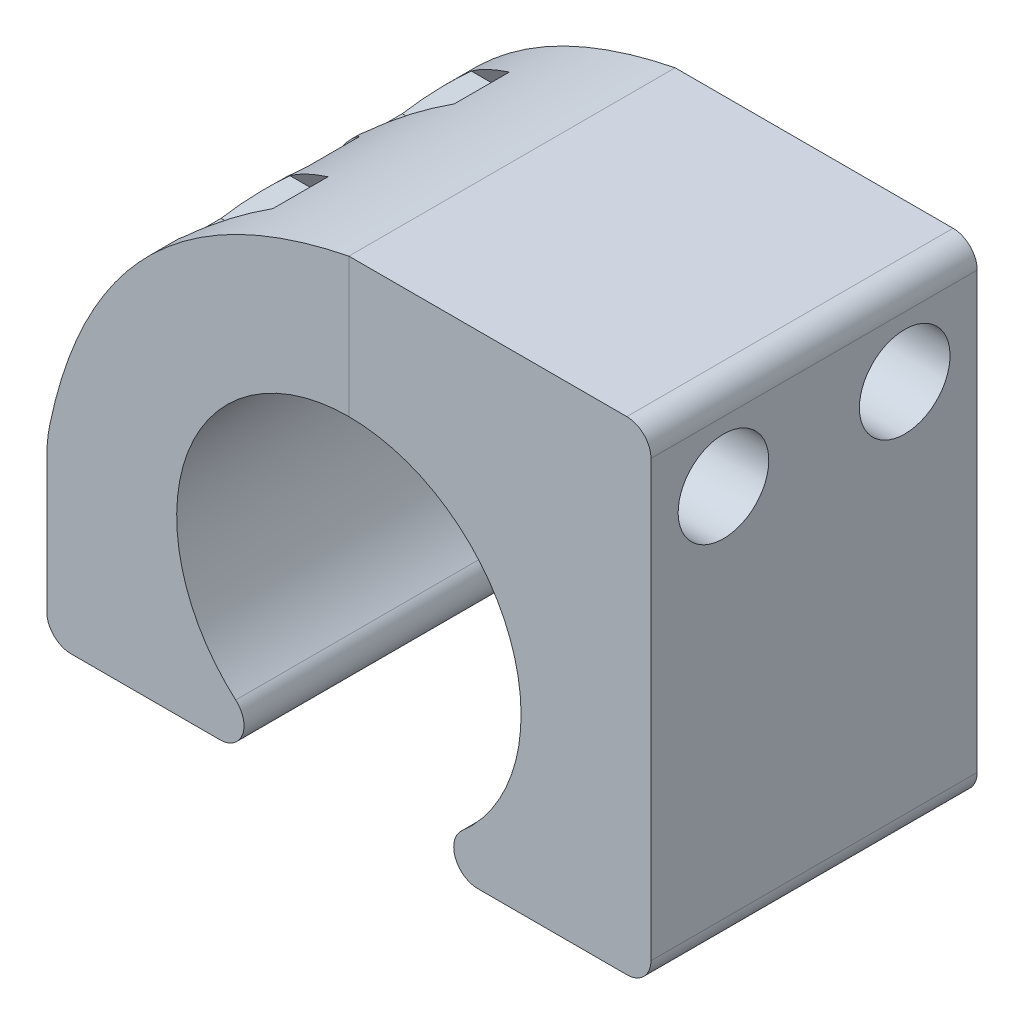
SolidWorks part; units mm, degrees
ref_plane "Front Plane" through (0, 0, 0) normal (0, 0, 1) x (1, 0, 0)
ref_plane "Top Plane" through (0, 0, 0) normal (0, 1, 0) x (1, 0, 0)
ref_plane "Right Plane" through (0, 0, 0) normal (1, 0, 0) x (0, 0, -1)
sketch "Sketch1" plane through (0, 0, 0) normal (0, 0, 1) x (1, 0, 0)
  line L0 (10.6771, -14.25) -> (25, -14.25)
  line L1 (-25, -14.25) -> (-10.6771, -14.25)
  line L2 (-25, -14.25) -> (-25, 25.75)
  line L3 (-25, 25.75) -> (25, 25.75)
  line L4 (25, -14.25) -> (25, 25.75)
  arc A0 (9.363, -10.7423) -> (-9.363, -10.7423) centre (0, 0) ccw
  arc A1 (9.363, -10.7423) -> (10.6771, -14.25) centre (10.6771, -12.25) ccw
  arc A2 (-9.363, -10.7423) -> (-10.6771, -14.25) centre (-10.6771, -12.25) cw
  point P4 (0, 25.75)
  point P9 (0, -14.25)
  dimension "D1" = 28.5
  dimension "D5" = 2
  dimension "D6" = 50
  dimension "D2" = 40
  dimension "D3" = 14.25
  dimension "D4" = 14.25
extrude "Boss-Extrude1" add sketch "Sketch1" along normal mid plane 27
sketch "Sketch2" plane through (0, 0, 13.5) normal (0, 0, 1) x (1, 0, 0)
  line L0 (0, 25.75) -> (0, 0)
  line L1 (25, 25.75) -> (-25, 25.75) construction
fillet "Fillet1" radius 2 3 edges at (25, -14.25, 0) (25, 25.75, 0) (-25, -14.25, 0)
split "Split1" trim tools "Sketch2" bodies to split 101 resulting bodies 102 103
sketch "Sketch3" plane through (25, 0, 0) normal (1, 0, 0) x (0, 0, -1)
  line L0 (-13.5, 25.75) -> (13.5, 25.75) construction
  line L1 (0, 0) -> (0, 23.0503) construction
  circle A0 centre (-7.5, 18.75) radius 3.75
  circle A1 centre (7.5, 18.75) radius 3.75
  dimension "D1" = 7.5
  dimension "D2" = 7
  dimension "D3" = 15
extrude "Cut-Extrude1" cut sketch "Sketch3" against normal offset from surface (10 mm away) 15 up to face at (0, 20, 0)
sketch "Sketch7" plane through (15, 0, 0) normal (1, 0, 0) x (0, 0, -1)
  line L0 (0, 0) -> (0, 5.8858) construction
  circle A0 centre (-7.5, 18.75) radius 2.25
  circle A1 centre (7.5, 18.75) radius 2.25
  dimension "D1" = 4.5
extrude "Cut-Extrude3" cut sketch "Sketch7" against normal up to next (15 mm away)
sketch "Sketch6" plane through (0, 0, 13.5) normal (0, 0, 1) x (1, 0, 0)
  line L0 (-25, 25.75) -> (-25, -12.25) construction
  line L1 (0, 25.75) -> (-25, 25.75) construction
  line L2 (-25, 25.75) -> (-25, 0)
  line L3 (0, 25.75) -> (-25, 25.75)
  spline S0 degree 2 poles (0, 25.75) (-21.1639, 21.5385) (-25, 0) knots 0 0 0 1 1 1
extrude "Cut-Extrude2" cut sketch "Sketch6" against normal up to next (27 mm away)
fillet "Fillet2" radius 12 1 edges at (-25, 0, 0)
sketch "Sketch8" plane through (0, 0, 0) normal (1, 0, 0) x (0, 0, -1)
  circle A0 centre (7.5, 18.75) radius 2.25 construction
  circle A1 centre (-7.5, 18.75) radius 2.25 construction
  circle A2 centre (7.5, 18.75) radius 2.25
  circle A3 centre (-7.5, 18.75) radius 2.25
extrude "Cut-Extrude4" cut sketch "Sketch8" along direction (1, 0, 0) on the side against the normal up to surface (25 mm away)
sketch "Sketch9" plane through (-25, 0, 0) normal (-1, 0, 0) x (0, 0, 1)
  line L0 (0, 0) -> (0, 7.3081) construction
  line L1 (-5.3349, 22.5) -> (-9.6651, 22.5)
  line L2 (-9.6651, 22.5) -> (-11.8301, 18.75)
  line L3 (-11.8301, 18.75) -> (-9.6651, 15)
  line L4 (-9.6651, 15) -> (-5.3349, 15)
  line L5 (-5.3349, 15) -> (-3.1699, 18.75)
  line L6 (-3.1699, 18.75) -> (-5.3349, 22.5)
  line L7 (3.1699, 18.75) -> (5.3349, 22.5)
  line L8 (5.3349, 15) -> (3.1699, 18.75)
  line L9 (9.6651, 15) -> (5.3349, 15)
  line L10 (11.8301, 18.75) -> (9.6651, 15)
  line L11 (9.6651, 22.5) -> (11.8301, 18.75)
  line L12 (5.3349, 22.5) -> (9.6651, 22.5)
  circle A0 centre (-7.5, 18.75) radius 3.75 construction
  circle A1 centre (7.5, 18.75) radius 3.75 construction
  point P10 (-7.5, 22.5)
  dimension "D1" = 7.5
extrude "Cut-Extrude5" cut sketch "Sketch9" against normal blind 15
sketch "Sketch10" plane through (0, -14.25, 0) normal (0, -1, 0) x (1, 0, 0)
  line L1 (0, -13.5) -> (0, 13.5) construction
  circle A0 centre (18.5, 0) radius 2.25 construction
  circle A1 centre (-18.5, 0) radius 2.25
  dimension "D1" = 4.5
  dimension "D2" = 37
extrude "Cut-Extrude6" cut sketch "Sketch10" against normal blind 35
sketch "Sketch11" plane through (0, 25.75, 0) normal (0, 1, 0) x (1, 0, 0)
  line L1 (-14.75, -2.1651) -> (-14.75, 2.1651)
  line L2 (-14.75, 2.1651) -> (-18.5, 4.3301)
  line L3 (-18.5, 4.3301) -> (-22.25, 2.1651)
  line L4 (-22.25, 2.1651) -> (-22.25, -2.1651)
  line L5 (-22.25, -2.1651) -> (-18.5, -4.3301)
  line L6 (-18.5, -4.3301) -> (-14.75, -2.1651)
  circle A0 centre (-18.5, 0) radius 3.75 construction
  point P10 (-14.75, 0)
  dimension "D1" = 7.5
extrude "Cut-Extrude7" cut sketch "Sketch11" against normal blind 17
other "Save Bodies1"
